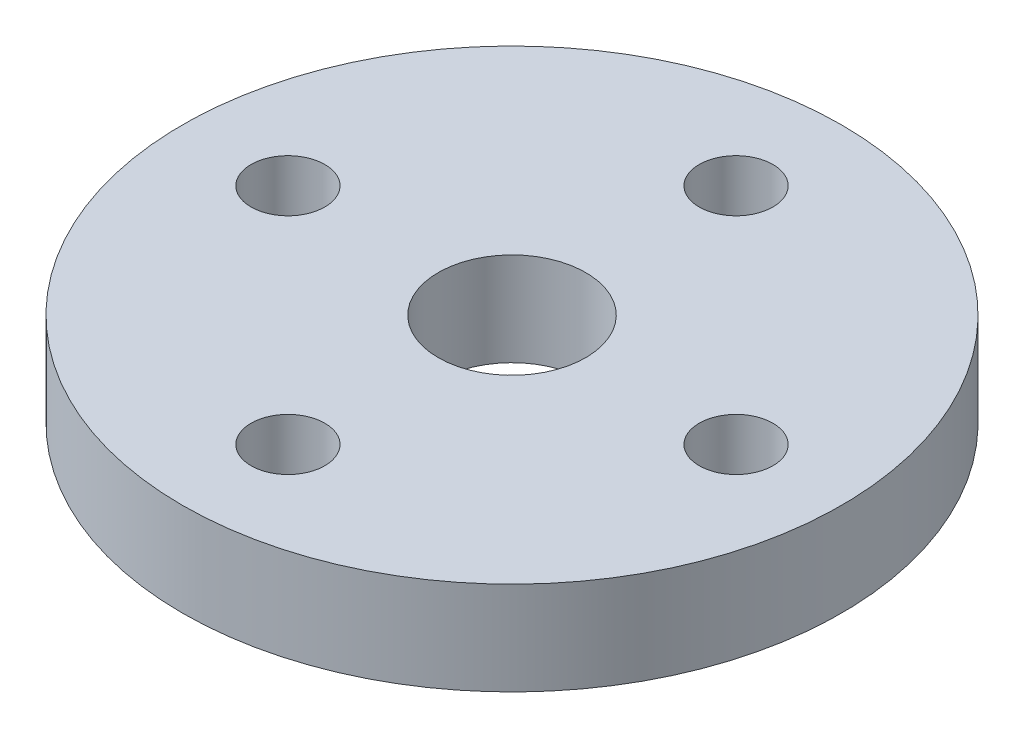
SolidWorks part; units mm, degrees
ref_plane "Front Plane" through (0, 0, 0) normal (0, 0, 1) x (1, 0, 0)
ref_plane "Top Plane" through (0, 0, 0) normal (0, 1, 0) x (1, 0, 0)
ref_plane "Right Plane" through (0, 0, 0) normal (1, 0, 0) x (0, 0, -1)
sketch "Sketch1" plane through (0, 0, 0) normal (0, 1, 0) x (1, 0, 0)
  line L0 (0, 17.65) -> (0, -17.65) construction
  line L1 (-17.65, 0) -> (17.65, 0) construction
  circle A0 centre (0, 0) radius 17.65
  circle A1 centre (0, 0) radius 3.95
  circle A2 centre (0, 12) radius 1.975
  circle A3 centre (-12, 0) radius 1.975
  circle A4 centre (12, 0) radius 1.975
  circle A5 centre (0, -12) radius 1.975
  dimension "D1" = 35.3
  dimension "D2" = 7.9
  dimension "D4" = 3.95
  dimension "D3" = 12
  dimension "D5" = 12
extrude "Boss-Extrude1" add sketch "Sketch1" along normal blind 5
